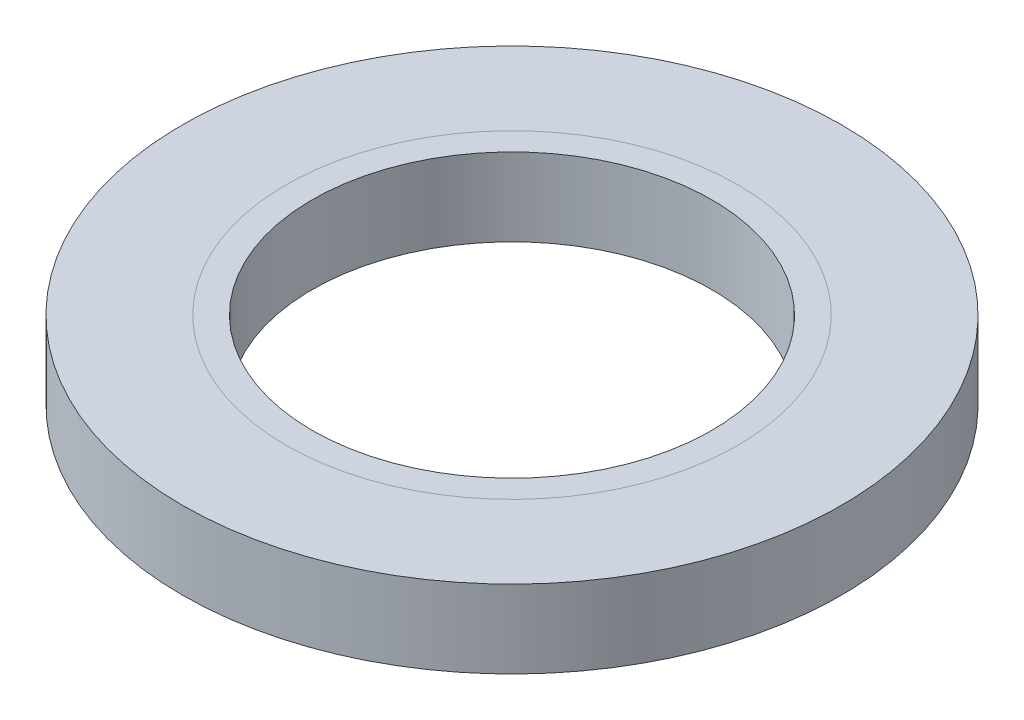
SolidWorks part; units mm, degrees
ref_plane "前视基准面" through (0, 0, 0) normal (0, 0, 1) x (1, 0, 0)
ref_plane "上视基准面" through (0, 0, 0) normal (0, 1, 0) x (1, 0, 0)
ref_plane "右视基准面" through (0, 0, 0) normal (1, 0, 0) x (0, 0, -1)
sketch "草图2" plane through (0, 0, 0) normal (0, 1, 0) x (1, 0, 0)
  circle A0 centre (0, 0) radius 38.5
  circle A1 centre (0, 0) radius 43.5
  dimension "D1" = 77
  dimension "D2" = 5
extrude "凸台-拉伸1" add sketch "草图2" along normal mid plane 15
sketch "草图3" plane through (0, 0, 0) normal (0, 1, 0) x (1, 0, 0)
  circle A0 centre (0, 0) radius 43.5
  circle A1 centre (0, 0) radius 63.5
  circle A2 centre (0, 0) radius 43.5 construction
  dimension "D1" = 20
extrude "凸台-拉伸2" add sketch "草图3" along normal mid plane 15 separate body
